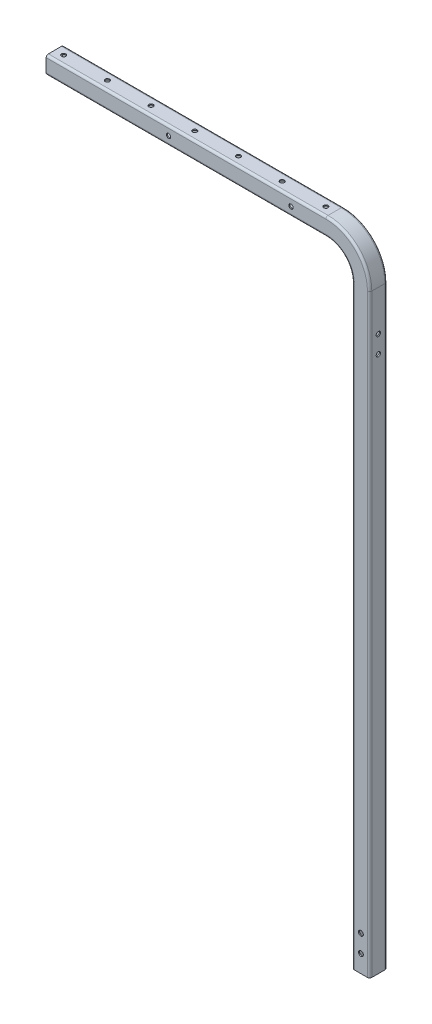
SolidWorks part; units mm, degrees
ref_plane "Front" through (0, 0, 0) normal (0, 0, 1) x (1, 0, 0)
ref_plane "Top" through (0, 0, 0) normal (0, 1, 0) x (1, 0, 0)
ref_plane "Right" through (0, 0, 0) normal (1, 0, 0) x (0, 0, -1)
sketch "Sketch1" plane through (0, 0, 0) normal (0, 0, 1) x (1, 0, 0)
  line L0 (0, 0) -> (406.4, 0)
  line L1 (457.2, -50.8) -> (457.2, -914.4)
  arc A0 (457.2, -50.8) -> (406.4, 0) centre (406.4, -50.8) ccw
  dimension "D1" = 50.8
  dimension "D2" = 457.2
  dimension "D3" = 914.4
sketch "Sketch2"
  line L0 (-12.7, 12.7) -> (12.7, 12.7)
  line L1 (-12.7, 12.7) -> (-12.7, -12.7)
  line L2 (12.7, -12.7) -> (-12.7, -12.7)
  line L3 (12.7, -12.7) -> (12.7, 12.7)
  line L4 (12.7, 12.7) -> (-12.7, -12.7) construction
  dimension "square" = 25.4
sweep "Base-Sweep" add profiles "Sketch2" path "Sketch1"
fillet "Fillet1" radius 3.175 12 edges at (451.3013, -5.8987, 12.7) (451.3013, -5.8987, -12.7) (433.3408, -23.8592, -12.7) (433.3408, -23.8592, 12.7) (469.9, -482.6, 12.7) (469.9, -482.6, -12.7) (444.5, -482.6, -12.7) (444.5, -482.6, 12.7) (203.2, 12.7, 12.7) (203.2, 12.7, -12.7) (203.2, -12.7, -12.7) (203.2, -12.7, 12.7)
shell "Shell1" thickness 1.5875
sketch "Sketch3" plane through (0, 12.7, 0) normal (0, 1, 0) x (-1, 0, 0)
  line L0 (0, 0) -> (-406.4, 0) construction
  line L1 (0, 9.525) -> (0, -9.525) construction
  circle A0 centre (-12.7, 0) radius 3.175
  dimension "D2" = 6.35
  dimension "D1" = 12.7
extrude "Wood Hole" cut sketch "Sketch3" against normal up to next
pattern_linear "LPattern1" count 7 spacing 63.5 along (1, 0, 0) of "Wood Hole"
sketch "Sketch5" plane through (469.9, 0, 0) normal (1, 0, 0) x (0, 0, -1)
  line L4 (-9.525, 12.7) -> (9.525, 12.7) construction
  line L5 (0, 50) -> (0, -50) construction
  circle A4 centre (0, -109.5375) radius 3.175
  circle A5 centre (0, -134.9375) radius 3.175
  dimension "D1" = 122.2375
  dimension "D3" = 6.35
  dimension "D2" = 25.4
extrude "cont_mtg" cut sketch "Sketch5" against normal through all
hole_wizard "1/4 (0.25) Diameter Hole1" positions "Sketch7" profile "Sketch6" hole size "1/4" standard "Ansi Inch" end condition through all
sketch "Sketch7" plane through (0, 0, 12.7) normal (0, 0, 1) x (1, 0, 0)
  line L1 (0, 9.525) -> (0, -9.525) construction
  line L2 (0, 0) -> (406.4, 0) construction
  point P0 (177.8, 0)
  point P1 (355.6, 0)
  dimension "D1" = 177.8
  dimension "D2" = 355.6
sketch "Sketch6" plane through (177.8, 0, 12.7) normal (1, 0, 0) x (0, -1, 0)
  line L0 (0, 0) -> (0, 25.4)
  line L1 (0, 25.4) -> (3.175, 25.4)
  line L2 (3.175, 25.4) -> (3.175, 0)
  line L5 (3.175, 0) -> (0, 0)
  line L11 (0, -6.35) -> (0, 107.95) construction
  dimension "Thru Hole Dia." = 6.35
  dimension "Thru Hole Depth" = 25.4
sketch "Sketch8" plane through (0, 0, -12.7) normal (0, 0, -1) x (-1, 0, 0)
  line L1 (-447.675, -914.4) -> (-466.725, -914.4) construction
  line L2 (-457.2, -50.8) -> (-457.2, -914.4) construction
  circle A1 centre (-457.2, -889) radius 3.5719
  dimension "D1" = 7.1437
  dimension "D3" = 25.4
extrude "Cut-Extrude1" cut sketch "Sketch8" against normal through all
pattern_linear "LPattern2" count 2 spacing 25.4 along (0, 1, 0) of "Cut-Extrude1"
